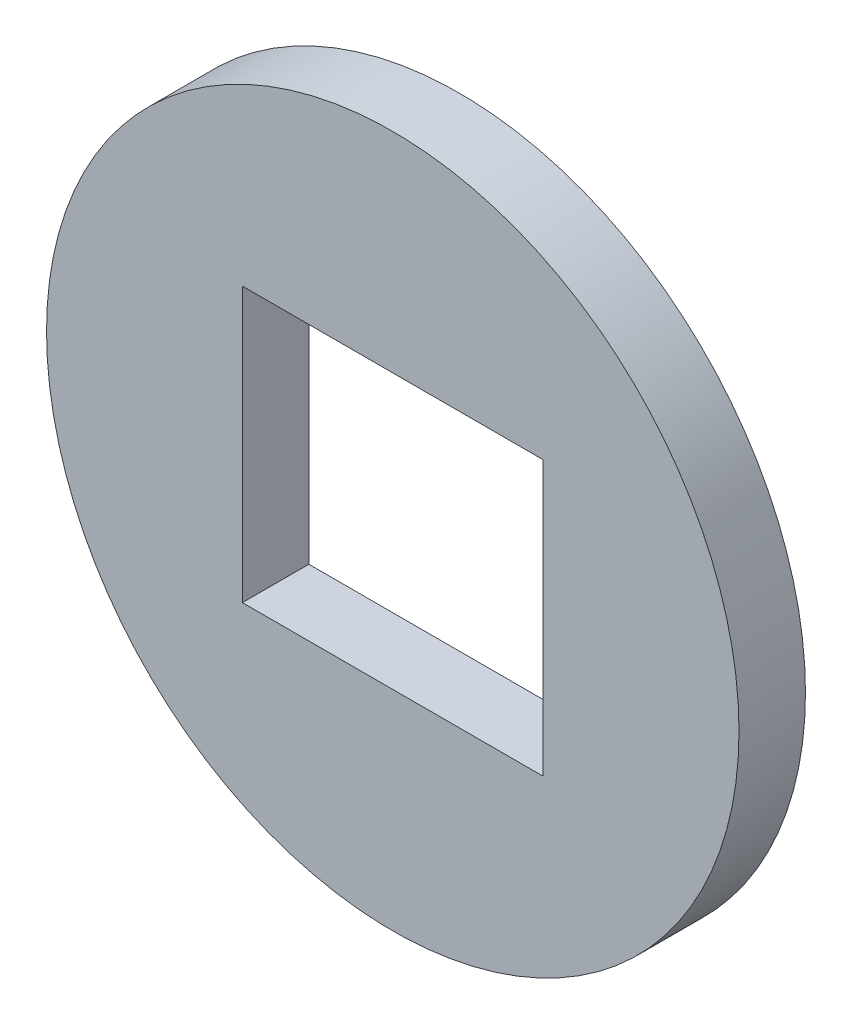
SolidWorks part; units mm, degrees
ref_plane "Front Plane" through (0, 0, 0) normal (0, 0, 1) x (1, 0, 0)
ref_plane "Top Plane" through (0, 0, 0) normal (0, 1, 0) x (1, 0, 0)
ref_plane "Right Plane" through (0, 0, 0) normal (1, 0, 0) x (0, 0, -1)
sketch "Sketch1" plane through (0, 0, 0) normal (0, 0, 1) x (1, 0, 0)
  circle A0 centre (0, 0) radius 52.1051
extrude "Boss-Extrude1" add sketch "Sketch1" along normal blind 10
sketch "Sketch2" plane through (0, 0, 10) normal (0, 0, 1) x (1, 0, 0)
  line L1 (-22.6318, -20.6242) -> (22.6318, -20.6242)
  line L2 (-22.6318, -20.6242) -> (-22.6318, 20.6242)
  line L3 (-22.6318, 20.6242) -> (22.6318, 20.6242)
  line L4 (22.6318, -20.6242) -> (22.6318, 20.6242)
  line L5 (-22.6318, -20.6242) -> (22.6318, 20.6242) construction
  line L6 (-22.6318, 20.6242) -> (22.6318, -20.6242) construction
  point P0 (0, 0)
extrude "Cut-Extrude1" cut sketch "Sketch2" against normal through all
